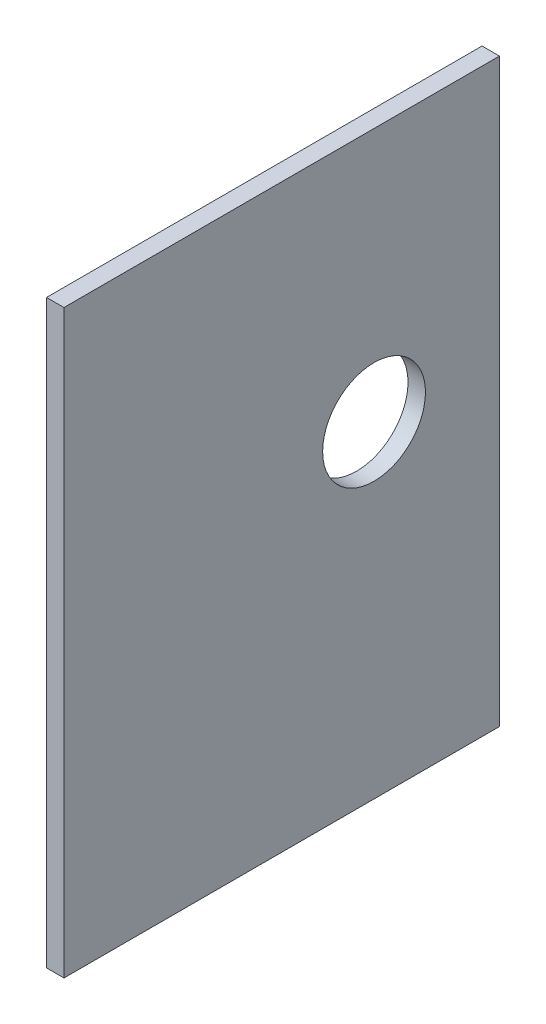
SolidWorks part; units mm, degrees
ref_plane "Front Plane" through (0, 0, 0) normal (0, 0, 1) x (1, 0, 0)
ref_plane "Top Plane" through (0, 0, 0) normal (0, 1, 0) x (1, 0, 0)
ref_plane "Right Plane" through (0, 0, 0) normal (1, 0, 0) x (0, 0, -1)
sketch "Sketch1" plane through (0, 0, 0) normal (1, 0, 0) x (0, 0, -1)
  line L0 (0, 0) -> (40.3863, 15.8371) construction
  line L1 (-95.25, -127) -> (95.25, -127)
  line L2 (-95.25, -127) -> (-95.25, 127)
  line L3 (-95.25, 127) -> (95.25, 127)
  line L4 (95.25, -127) -> (95.25, 127)
  line L5 (-95.25, -127) -> (95.25, 127) construction
  line L6 (-95.25, 127) -> (95.25, -127) construction
  circle A0 centre (40.3863, 15.8371) radius 22.479
  point P0 (0, 0)
  point P8 (42.5142, -16.5669)
  point P9 (40.3863, 15.8371)
  dimension "D1" = 44.958
  dimension "D2" = 190.5
  dimension "D3" = 254
extrude "Boss-Extrude1" add sketch "Sketch1" along normal blind 7.62
